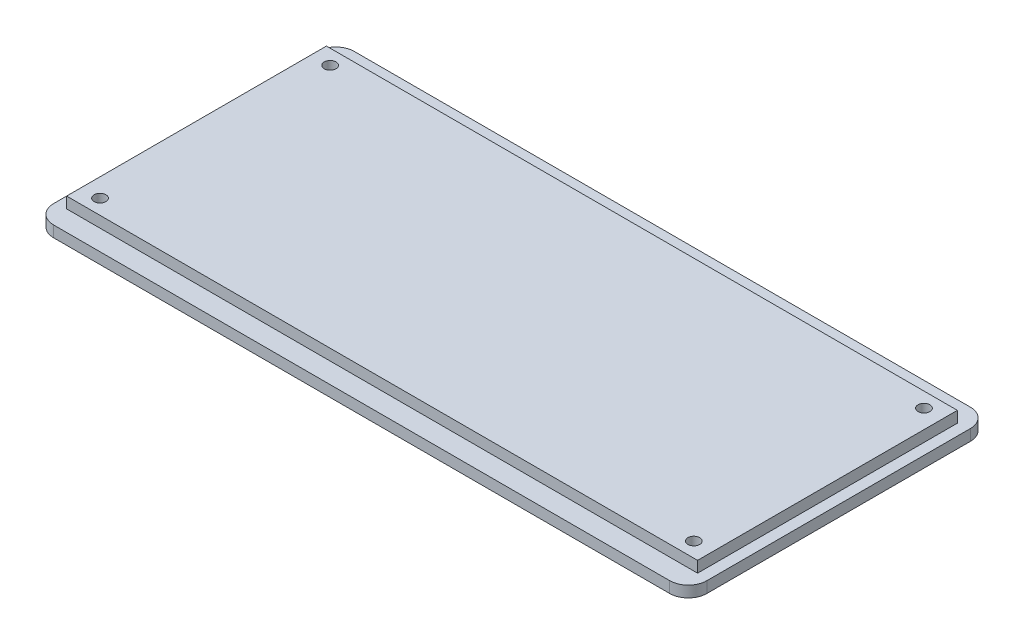
SolidWorks part; units mm, degrees
ref_plane "Front Plane" through (0, 0, 0) normal (0, 0, 1) x (1, 0, 0)
ref_plane "Top Plane" through (0, 0, 0) normal (0, 1, 0) x (1, 0, 0)
ref_plane "Right Plane" through (0, 0, 0) normal (1, 0, 0) x (0, 0, -1)
sketch "Sketch1" plane through (0, 0, 0) normal (0, 1, 0) x (1, 0, 0)
  line L1 (-88, 40.5) -> (88, 40.5)
  line L2 (-88, 40.5) -> (-88, -40.5)
  line L3 (-88, -40.5) -> (88, -40.5)
  line L4 (88, 40.5) -> (88, -40.5)
  line L5 (-88, 40.5) -> (88, -40.5) construction
  line L6 (-88, -40.5) -> (88, 40.5) construction
  point P0 (0, 0)
  dimension "D1" = 176
  dimension "D2" = 81
extrude "Boss-Extrude1" add sketch "Sketch1" along normal blind 3 contours L2 L3 L4 L1
fillet "Fillet1" radius 5 4 edges at (88, 1.5, -40.5) (88, 1.5, 40.5) (-88, 1.5, -40.5) (-88, 1.5, 40.5)
sketch "Sketch2" plane through (0, 0, 0) normal (0, -1, 0) x (1, 0, 0)
  line L1 (-85, -35) -> (85, -35)
  line L2 (-85, -35) -> (-85, 35)
  line L3 (-85, 35) -> (85, 35)
  line L4 (85, -35) -> (85, 35)
  line L5 (-85, -35) -> (85, 35) construction
  line L6 (-85, 35) -> (85, -35) construction
  point P0 (0, 0)
  dimension "D1" = 170
  dimension "D2" = 70
extrude "Boss-Extrude2" add sketch "Sketch2" against normal blind 6
sketch "Sketch3" plane through (0, 6, 0) normal (0, 1, 0) x (1, 0, 0)
  line L0 (-85, -35) -> (-85, 35) construction
  line L1 (-85, 35) -> (85, 35) construction
  circle A0 centre (-80, 31) radius 1.6
  dimension "D1" = 3.2
  dimension "D2" = 5
  dimension "D3" = 4
extrude "Cut-Extrude1" cut sketch "Sketch3" against normal through all
sketch "Sketch5" plane through (0, 0, 0) normal (0, -1, 0) x (1, 0, 0)
  circle A0 centre (-80, -31) radius 3
  dimension "D1" = 6
extrude "Cut-Extrude5" cut sketch "Sketch5" against normal blind 2
mirror "Mirror1" about plane through (0, 0, 0) normal (0, 0, 1) of "Cut-Extrude5", "Cut-Extrude1"
mirror "Mirror2" about plane through (0, 0, 0) normal (1, 0, 0) of "Mirror1", "Cut-Extrude1", "Cut-Extrude5"
